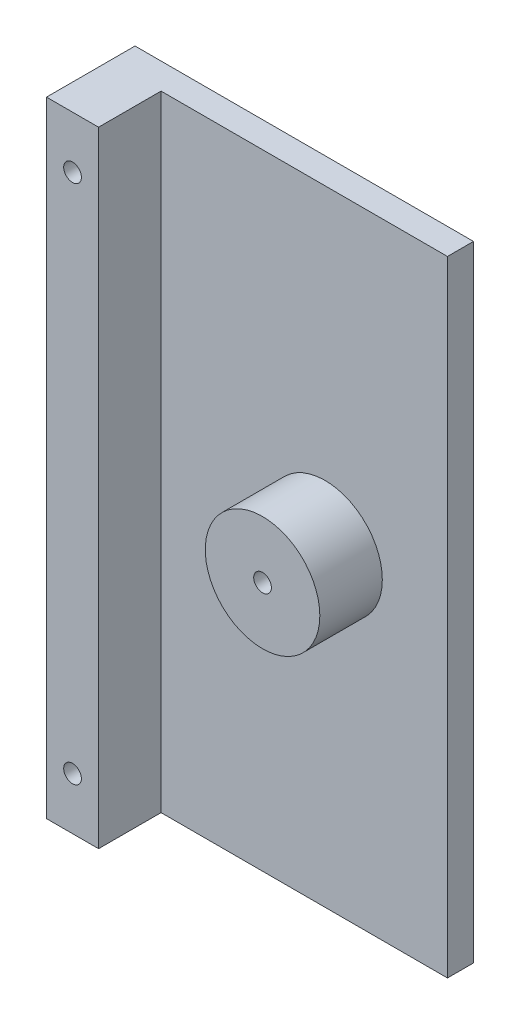
SolidWorks part; units mm, degrees
ref_plane "Front Plane" through (0, 0, 0) normal (1, 0, 0) x (0, 1, 0)
ref_plane "Top Plane" through (0, 0, 0) normal (0, 0, 1) x (0, 1, 0)
ref_plane "Right Plane" through (0, 0, 0) normal (0, 1, 0) x (-1, 0, 0)
sketch "Sketch1" plane through (0, 0, 0) normal (0, 0, 1) x (0, 1, 0)
  line L1 (60, -32.5) -> (-60, -32.5)
  line L2 (60, -32.5) -> (60, 32.5)
  line L3 (60, 32.5) -> (-60, 32.5)
  line L4 (-60, -32.5) -> (-60, 32.5)
  line L5 (60, -32.5) -> (-60, 32.5) construction
  line L6 (60, 32.5) -> (-60, -32.5) construction
  point P0 (0, 0)
  dimension "D1" = 65
  dimension "D2" = 120
extrude "Boss-Extrude1" add sketch "Sketch1" along normal blind 5
sketch "Sketch2" plane through (0, 0, 5) normal (0, 0, 1) x (1, 0, 0)
  line L0 (-32.5, -60) -> (32.5, -60) construction
  line L1 (-32.5, 60) -> (-22.5, 60)
  line L2 (-32.5, 60) -> (-32.5, -60)
  line L3 (-32.5, -60) -> (-22.5, -60)
  line L4 (-22.5, 60) -> (-22.5, -60)
  dimension "D1" = 10
extrude "Boss-Extrude2" add sketch "Sketch2" along normal blind 12
sketch "Sketch3" plane through (0, 0, 5) normal (0, 0, 1) x (1, 0, 0)
  line L0 (-22.5, -60) -> (32.5, -60) construction
  line L1 (32.5, -60) -> (32.5, 60) construction
  circle A0 centre (8.99, 0) radius 11
  dimension "D1" = 22
  dimension "D2" = 60
  dimension "D3" = 23.51
extrude "Boss-Extrude3" add sketch "Sketch3" along normal blind 12
sketch "Sketch4" plane through (0, 0, 17) normal (0, 0, 1) x (1, 0, 0)
  line L0 (-32.5, -60) -> (-22.5, -60) construction
  line L1 (-22.5, 60) -> (-32.5, 60) construction
  line L2 (-32.5, 60) -> (-32.5, -60) construction
  circle A0 centre (-27.5, 50) radius 1.7
  circle A1 centre (-27.5, -50) radius 1.7
  dimension "D1" = 3.4
  dimension "D2" = 3.4
  dimension "D3" = 10
  dimension "D4" = 10
  dimension "D5" = 5
  dimension "D6" = 5
extrude "Cut-Extrude1" cut sketch "Sketch4" against normal blind 22
sketch "Sketch5" plane through (0, 0, 17) normal (0, 0, 1) x (1, 0, 0)
  circle A0 centre (8.99, 0) radius 1.7
  dimension "D1" = 3.4
extrude "Cut-Extrude2" cut sketch "Sketch5" against normal blind 17
sketch "Sketch6" plane through (0, 0, 0) normal (0, 0, -1) x (1, 0, 0)
  line L1 (7.3838, -2.8723) -> (10.6744, -2.8272)
  line L2 (10.6744, -2.8272) -> (12.2806, 0.0452)
  line L3 (12.2806, 0.0452) -> (10.5962, 2.8723)
  line L4 (10.5962, 2.8723) -> (7.3056, 2.8272)
  line L5 (7.3056, 2.8272) -> (5.6994, -0.0452)
  line L6 (5.6994, -0.0452) -> (7.3838, -2.8723)
  circle A0 centre (8.99, 0) radius 2.85 construction
  dimension "D1" = 5.7
extrude "Cut-Extrude3" cut sketch "Sketch6" against normal blind 2.6
